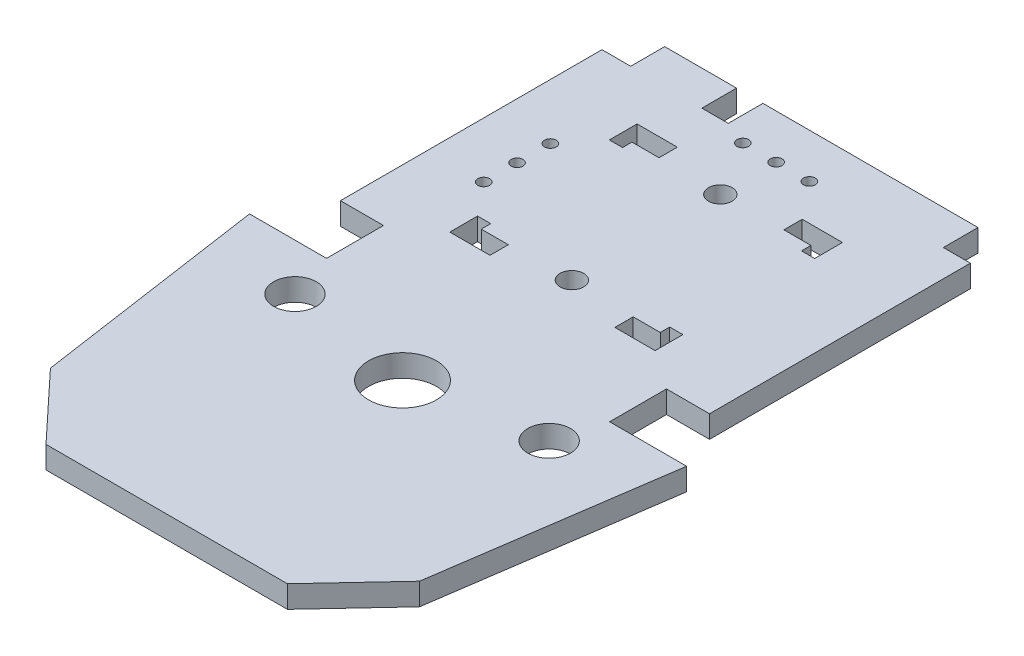
SolidWorks part; units mm, degrees
ref_plane "Front Plane" through (0, 0, 0) normal (0, 0, 1) x (1, 0, 0)
ref_plane "Top Plane" through (0, 0, 0) normal (0, 1, 0) x (1, 0, 0)
ref_plane "Right Plane" through (0, 0, 0) normal (1, 0, 0) x (0, 0, -1)
sketch "Sketch1" plane through (0, 0, 0) normal (0, 1, 0) x (1, 0, 0)
  line L0 (0, 0) -> (26.6, 0) construction
  line L1 (0, 0) -> (0, -47.12) construction
  line L2 (0, -47.12) -> (26.6, -47.12) construction
  line L3 (26.6, -47.12) -> (26.6, 0) construction
  line L4 (2.07, 0) -> (24.65, 0) construction
  line L5 (19.35, 0) -> (19.35, -2.5) construction
  line L6 (19.35, -2.5) -> (17.45, -2.5) construction
  line L7 (17.45, -2.5) -> (17.45, 0) construction
  line L8 (17.45, 0) -> (2.07, 0) construction
  line L9 (2.07, 0) -> (2.07, -2.45)
  line L10 (2.07, -2.45) -> (0, -2.45)
  line L11 (0, -2.45) -> (0, -21.3)
  line L12 (0, -25.4) -> (-2.45, -25.4)
  line L13 (0, -42.2) -> (4.6, -47.12)
  line L14 (4.6, -47.12) -> (22, -47.12)
  line L15 (22, -47.12) -> (26.6, -42.2)
  line L16 (26.6, -25.4) -> (29.05, -25.4)
  line L17 (26.6, -21.3) -> (26.6, -2.5)
  line L18 (26.6, -2.5) -> (24.65, -2.5)
  line L19 (24.65, -2.5) -> (24.65, 0)
  line L20 (24.65, 0) -> (19.35, 0)
  line L21 (0, -21.3) -> (3.1, -21.3)
  line L22 (3.1, -21.3) -> (3.1, -25.4)
  line L23 (3.1, -25.4) -> (0, -25.4)
  line L24 (26.6, -25.4) -> (23.5, -25.4)
  line L25 (23.5, -25.4) -> (23.5, -21.3)
  line L26 (23.5, -21.3) -> (26.6, -21.3)
  line L27 (20.7, -19.32) -> (20.7, -17.32)
  line L28 (0, -23.56) -> (26.6, -23.56) construction
  line L29 (17.8, -18) -> (17.8, -19.32)
  line L30 (19.75, -18) -> (19.75, -17.32)
  line L31 (19.75, -17.32) -> (20.7, -17.32)
  line L32 (19.75, -18) -> (17.8, -18)
  line L33 (17.8, -19.32) -> (20.7, -19.32)
  line L34 (13.3, -35.8804) -> (13.3, -53.9532) construction
  line L35 (8.8, -19.32) -> (5.9, -19.32)
  line L36 (6.85, -18) -> (8.8, -18)
  line L37 (6.85, -17.32) -> (5.9, -17.32)
  line L38 (6.85, -18) -> (6.85, -17.32)
  line L39 (8.8, -18) -> (8.8, -19.32)
  line L40 (5.9, -19.32) -> (5.9, -17.32)
  line L41 (0, -12.57) -> (26.6, -12.57) construction
  line L42 (17.8, -5.82) -> (20.7, -5.82)
  line L43 (19.75, -7.14) -> (17.8, -7.14)
  line L44 (19.75, -7.82) -> (20.7, -7.82)
  line L45 (19.75, -7.14) -> (19.75, -7.82)
  line L46 (17.8, -7.14) -> (17.8, -5.82)
  line L47 (20.7, -5.82) -> (20.7, -7.82)
  line L48 (5.9, -5.82) -> (5.9, -7.82)
  line L49 (8.8, -7.14) -> (8.8, -5.82)
  line L50 (6.85, -7.14) -> (6.85, -7.82)
  line L51 (6.85, -7.82) -> (5.9, -7.82)
  line L52 (6.85, -7.14) -> (8.8, -7.14)
  line L53 (8.8, -5.82) -> (5.9, -5.82)
  line L54 (10.9, -3.2) -> (13.3, -3.2) construction
  line L55 (13.3, -3.2) -> (15.7, -3.2) construction
  line L56 (22.6, -10.17) -> (22.6, -12.57) construction
  line L57 (22.6, -12.57) -> (22.6, -14.97) construction
  line L58 (29.05, -25.4) -> (26.6, -42.2)
  line L59 (-2.45, -25.4) -> (0, -42.2)
  line L60 (7.25, -2.5) -> (9.15, -2.5)
  line L61 (7.25, 0) -> (7.25, -2.5)
  line L62 (9.15, -2.5) -> (9.15, 0)
  line L63 (2.07, 0) -> (7.25, 0)
  line L64 (9.15, 0) -> (24.65, 0)
  circle A0 centre (22.51, -28.768) radius 1.54
  circle A1 centre (4.19, -28.768) radius 1.54
  circle A2 centre (13.4513, -30.2766) radius 2.4434
  circle A3 centre (13.3, -7.22) radius 0.85
  circle A4 centre (13.3, -17.92) radius 0.85
  circle A5 centre (13.3, -3.2) radius 0.425
  circle A6 centre (15.7, -3.2) radius 0.425
  circle A7 centre (10.9, -3.2) radius 0.425
  circle A8 centre (22.6, -12.57) radius 0.425 construction
  circle A9 centre (22.6, -10.17) radius 0.425 construction
  circle A10 centre (22.6, -14.97) radius 0.425 construction
  circle A11 centre (4, -14.97) radius 0.425
  circle A12 centre (4, -12.57) radius 0.425
  circle A13 centre (4, -10.17) radius 0.425
  point P9 (26.6, -21.3)
  point P12 (26.6, -2.5)
  point P13 (26.6, -25.4)
  point P14 (0, -2.45)
  point P15 (0, -21.3)
  point P16 (0, -25.4)
  point P17 (26.6, -42.2)
  point P18 (22, -47.12)
  point P19 (4.6, -47.12)
  point P20 (0, -42.2)
  point P34 (24.05, -28.768)
  point P43 (13.4513, -32.72)
  dimension "D19" = 3.08
  dimension "D20" = 2
  dimension "D21" = 15.24
  dimension "D22" = 9.5
  dimension "D24" = 5.4
  dimension "D25" = 5.2
  dimension "D26" = 2.9
  dimension "D18" = 5.9
  dimension "D31" = 9
  dimension "D32" = 1.7
  dimension "D33" = 0.85
  dimension "D1" = 26.6
  dimension "D2" = 47.12
  dimension "D3" = 22.58
  dimension "D4" = 5.3
  dimension "D5" = 1.9
  dimension "D6" = 1.95
  dimension "D7" = 2.07
  dimension "D8" = 18.8
  dimension "D9" = 2.5
  dimension "D10" = 2.5
  dimension "D11" = 4.1
  dimension "D12" = 2.45
  dimension "D14" = 3.1
  dimension "D15" = 4.6
  dimension "D16" = 4.6
  dimension "D17" = 2.55
  dimension "D23" = 14.4
  dimension "D27" = 2
  dimension "D28" = 0.95
  dimension "D29" = 1.32
  dimension "D30" = 27.8
  dimension "D34" = 4.8
  dimension "D35" = 3.2
  dimension "D36" = 4
  dimension "D37" = 31.5
  dimension "D38" = 4.92
extrude "Boss-Extrude1" add sketch "Sketch1" along normal blind 1.6 contours L64 L62 L60 L61 L63 L9 L10 L11 L21 L22 L23 L12 L59 L13 L14 L15 L58 L16 L24 L25 L26 L17 L18 L19 L20 A12 A4 A3 A2 A1 A0 L53 L49 L52 L50 L51 L48 L33 L29 L32 L30 L31 L27
